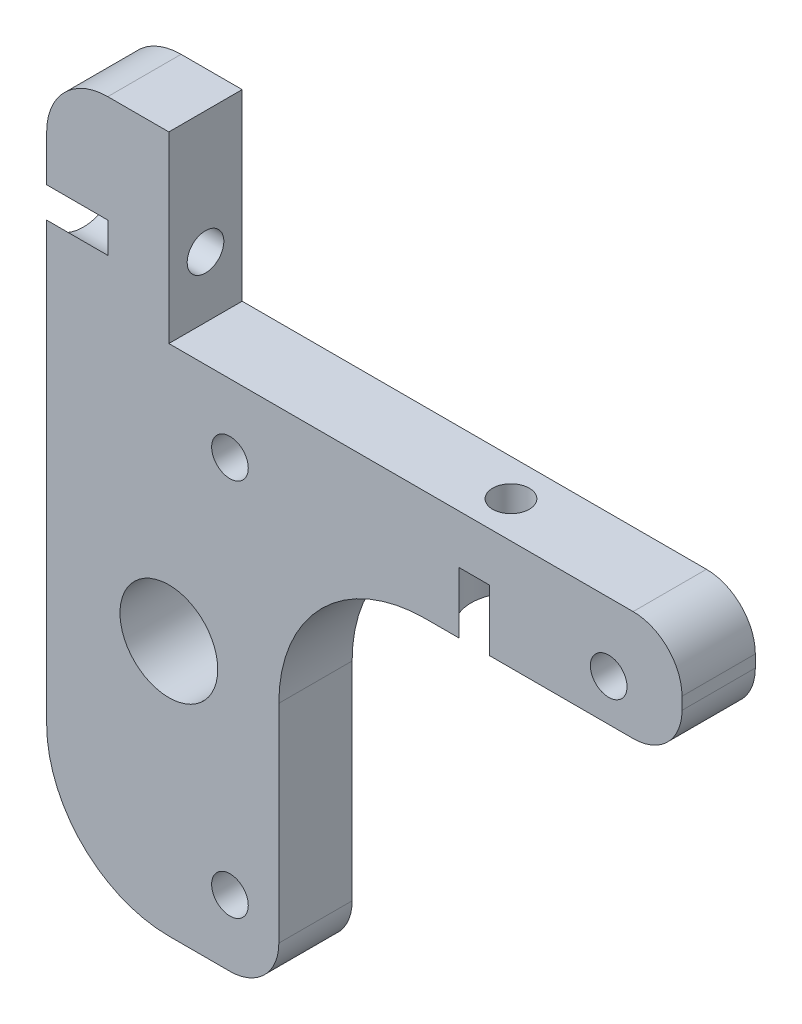
SolidWorks part; units mm, degrees
ref_plane "Alzado" through (0, 0, 0) normal (0, 0, 1) x (1, 0, 0)
ref_plane "Planta" through (0, 0, 0) normal (0, 1, 0) x (1, 0, 0)
ref_plane "Vista lateral" through (0, 0, 0) normal (1, 0, 0) x (0, 0, -1)
sketch "Croquis1" plane through (0, 0, 0) normal (0, 0, 1) x (1, 0, 0)
  line L0 (0, 0) -> (38, 0)
  line L1 (42, -4) -> (42, -5)
  line L2 (38, -9) -> (21, -9)
  line L3 (9, -21) -> (9, -38)
  line L4 (5, -42) -> (0, -42)
  line L5 (-10, -32) -> (-10, 10)
  line L6 (-5, 15) -> (0, 15)
  line L7 (0, 15) -> (0, 0)
  arc A1 (9, -21) -> (21, -9) centre (21, -21) cw
  circle A2 centre (36, -5.58) radius 1.5
  circle A3 centre (5, -5.58) radius 1.5
  circle A4 centre (5, -36.58) radius 1.5
  circle A5 centre (0, -21.1) radius 4
  arc A6 (0, -42) -> (-10, -32) centre (0, -32) cw
  arc A7 (-10, 10) -> (-5, 15) centre (-5, 10) cw
  arc A8 (42, -5) -> (38, -9) centre (38, -5) cw
  arc A9 (38, 0) -> (42, -4) centre (38, -4) cw
  arc A10 (9, -38) -> (5, -42) centre (5, -38) cw
  dimension "D7" = 21.1
  dimension "D8" = 12
  dimension "D9" = 3
  dimension "D10" = 3
  dimension "D11" = 3
  dimension "D14" = 8
  dimension "D15" = 10
  dimension "D16" = 5
  dimension "D17" = 4
  dimension "D18" = 4
  dimension "D1" = 42
  dimension "D2" = 42
  dimension "D3" = 9
  dimension "D4" = 19
  dimension "D5" = 15
  dimension "D6" = 10
  dimension "D12" = 5.58
  dimension "D13" = 15
  dimension "D19" = 31
  dimension "D20" = 31
extrude "Saliente-Extruir1" add sketch "Croquis1" along normal blind 6
fillet "Redondeo1" [suppressed] radius 1
sketch "Croquis2" [suppressed] plane through (-10, 0, 0) normal (-1, 0, 0) x (0, 0, 1)
  line L0 (-15, 9) -> (-15, 1) construction
  line L1 (-10, 10) -> (32, 10) construction
  circle A0 centre (-7.5, 5) radius 1.5
  dimension "D1" = 3
  dimension "D2" = 7.5
  dimension "D3" = 5
extrude "Cortar-Extruir1" [suppressed] cut sketch "Croquis2" against normal through all
sketch "Croquis3" [suppressed] plane through (0, 0, 10) normal (0, 0, 1) x (1, 0, 0)
  line L0 (21, 10) -> (38, 10) construction
  line L1 (42, 9) -> (42, 1) construction
  circle A0 centre (27, 5) radius 1.5
  dimension "D1" = 3
  dimension "D2" = 5
  dimension "D3" = 15
extrude "Cortar-Extruir2" [suppressed] cut sketch "Croquis3" against normal through all
sketch "Croquis4" plane through (0, -9, 0) normal (0, -1, 0) x (1, 0, 0)
  line L0 (21, 0) -> (38, 0) construction
  line L2 (0, 6) -> (0, 0) construction
  circle A0 centre (25, 3) radius 1.5
  dimension "D1" = 3
  dimension "D2" = 3
  dimension "D3" = 25
extrude "Cortar-Extruir3" cut sketch "Croquis4" against normal through all
sketch "Croquis5" plane through (-10, 0, 0) normal (-1, 0, 0) x (0, 0, 1)
  line L0 (0, 10) -> (0, -32) construction
  line L1 (6, 15) -> (0, 15) construction
  circle A0 centre (3, 5) radius 1.5
  dimension "D1" = 3
  dimension "D2" = 3
  dimension "D3" = 10
extrude "Cortar-Extruir4" cut sketch "Croquis5" against normal through all
sketch "Croquis6" plane through (0, -9, 0) normal (0, -1, 0) x (1, 0, 0)
  circle A0 centre (25, 3) radius 3.25
  dimension "D1" = 6.5
extrude "Cortar-Extruir5" cut sketch "Croquis6" against normal blind 5
sketch "Croquis7" plane through (-10, 0, 0) normal (-1, 0, 0) x (0, 0, 1)
  circle A0 centre (3, 5) radius 3.25
  dimension "D1" = 6.5
extrude "Cortar-Extruir6" cut sketch "Croquis7" against normal blind 5
